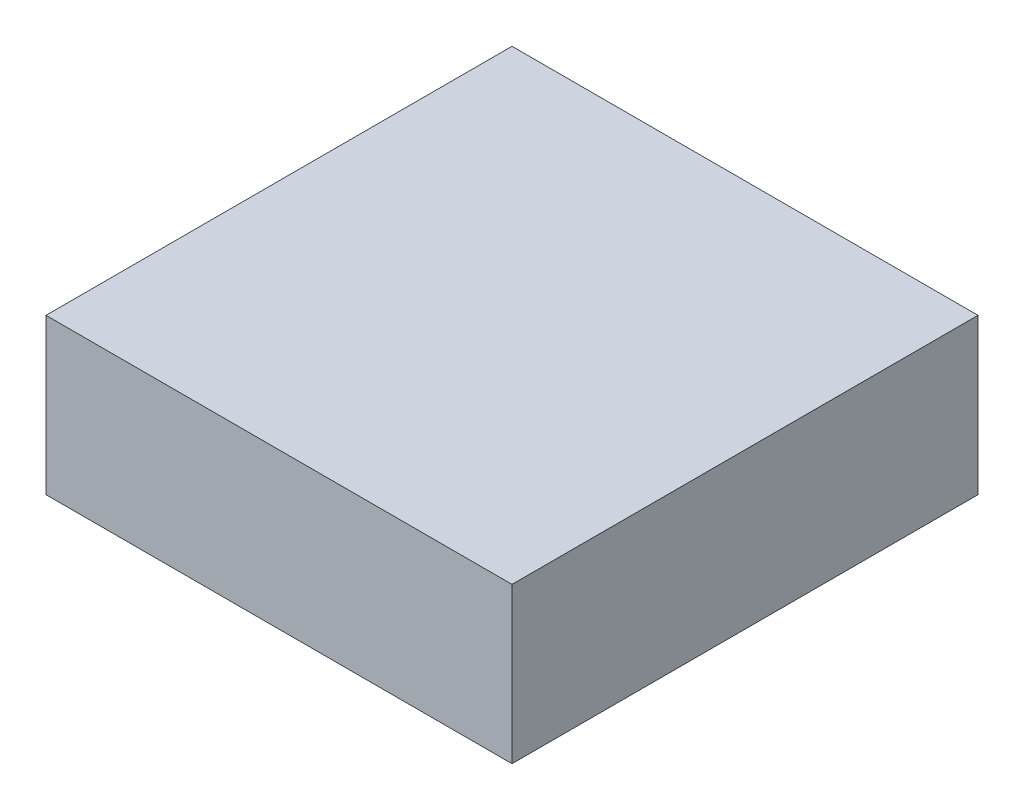
SolidWorks part; units mm, degrees
ref_plane "前视基准面" through (0, 0, 0) normal (0, 0, 1) x (1, 0, 0)
ref_plane "上视基准面" through (0, 0, 0) normal (0, 1, 0) x (1, 0, 0)
ref_plane "右视基准面" through (0, 0, 0) normal (1, 0, 0) x (0, 0, -1)
other "Configuration Table"
sketch "草图1" plane through (0, 0, 0) normal (0, 0, 1) x (1, 0, 0)
  line L0 (0, 0) -> (36, 0)
  line L1 (36, 0) -> (36, 12)
  line L2 (36, 12) -> (0, 12)
  line L3 (0, 12) -> (0, 0)
  dimension "width" = 36
  dimension "height" = 12
extrude "Lower_support" add sketch "草图1" along normal blind 36
